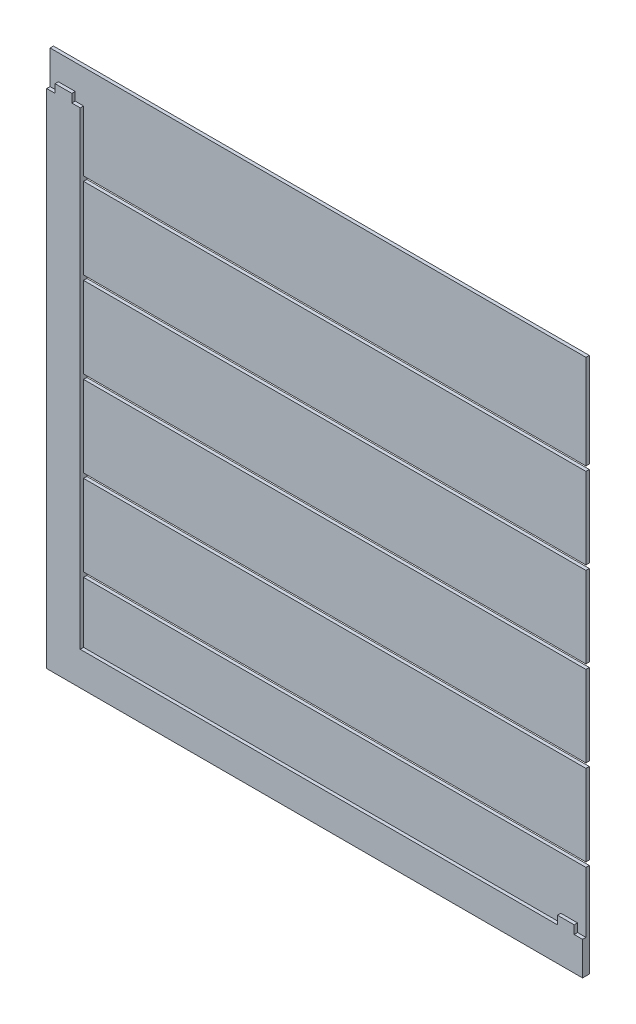
SolidWorks part; units mm, degrees
ref_plane "前视基准面" through (0, 0, 0) normal (0, 0, 1) x (1, 0, 0)
ref_plane "上视基准面" through (0, 0, 0) normal (0, 1, 0) x (1, 0, 0)
ref_plane "右视基准面" through (0, 0, 0) normal (1, 0, 0) x (0, 0, -1)
sketch "草图1" plane through (0, 0, 0) normal (0, 0, 1) x (1, 0, 0)
  line L0 (-75, 51.8686) -> (75, 51.8686)
  line L5 (75, 79.9686) -> (75, 51.8686)
  line L6 (75, 50.4686) -> (75, 26.2686)
  line L7 (-75, 50.4686) -> (75, 50.4686)
  line L8 (75, 24.8686) -> (75, 0.6686)
  line L9 (-75, 50.4686) -> (-75, 51.8686)
  line L10 (-75, 51.8686) -> (-75, 51.1686) construction
  line L11 (-75, 51.1686) -> (75, 51.1686) construction
  line L12 (-75, 51.8686) -> (75, 51.8686)
  line L13 (-75, 24.8686) -> (-75, 26.2686)
  line L14 (75, -0.7314) -> (75, -24.9314)
  line L15 (75, -26.3314) -> (75, -50.5314)
  line L16 (-65, 51.8686) -> (75, 51.8686)
  line L17 (-65, 50.4686) -> (75, 50.4686)
  line L18 (75, -51.9314) -> (75, -80.0314)
  line L19 (-65, 51.8686) -> (75, 51.8686)
  line L20 (-75, -0.7314) -> (-75, 0.6686)
  line L21 (-65, 51.1686) -> (75, 51.1686) construction
  line L22 (75, 79.9686) -> (-85, 79.9686)
  line L23 (-85, 79.9686) -> (-85, -80.0314)
  line L24 (-65, 26.2686) -> (75, 26.2686)
  line L25 (-65, 24.8686) -> (75, 24.8686)
  line L27 (-65, 26.2686) -> (75, 26.2686)
  line L29 (-65, 25.5686) -> (75, 25.5686) construction
  line L30 (-85, -80.0314) -> (75, -80.0314)
  line L32 (-65, 0.6686) -> (75, 0.6686)
  line L33 (-65, -0.7314) -> (75, -0.7314)
  line L35 (-65, 0.6686) -> (75, 0.6686)
  line L37 (-65, -0.0314) -> (75, -0.0314) construction
  line L45 (-65, -25.6314) -> (75, -25.6314) construction
  line L47 (-75, -26.3314) -> (-75, -24.9314)
  line L50 (-75, -0.0314) -> (-85, -0.0314) construction
  line L54 (-75, -51.9314) -> (-75, -50.5314)
  line L56 (-75, 26.2686) -> (75, 26.2686)
  line L57 (-75, 24.8686) -> (75, 24.8686)
  line L59 (-75, 26.2686) -> (75, 26.2686)
  line L61 (-75, 25.5686) -> (75, 25.5686) construction
  line L64 (-75, 0.6686) -> (75, 0.6686)
  line L65 (-75, -0.7314) -> (75, -0.7314)
  line L67 (-75, 0.6686) -> (75, 0.6686)
  line L69 (-75, -0.0314) -> (75, -0.0314) construction
  line L72 (-75, -24.9314) -> (75, -24.9314)
  line L73 (-75, -26.3314) -> (75, -26.3314)
  line L75 (-75, -24.9314) -> (75, -24.9314)
  line L77 (-75, -25.6314) -> (75, -25.6314) construction
  line L80 (-75, -50.5314) -> (75, -50.5314)
  line L81 (-75, -51.9314) -> (75, -51.9314)
  line L83 (-75, -50.5314) -> (75, -50.5314)
  line L85 (-75, -51.2314) -> (75, -51.2314) construction
  line L101 (-65, -26.3314) -> (75, -26.3314) [skipped]
  line L102 (-65, -24.9314) -> (75, -24.9314) [skipped]
  line L103 (-65, -24.9314) -> (75, -24.9314) [skipped]
  line L105 (-65, -50.5314) -> (75, -50.5314) [skipped]
  line L106 (-65, -50.5314) -> (75, -50.5314) [skipped]
  line L107 (-65, -51.9314) -> (75, -51.9314) [skipped]
  line L108 (-65, -51.2314) -> (75, -51.2314) construction
  point P0 (0, 0)
  point P3 (-85, -0.0314)
  dimension "D1" = 160
  dimension "D2" = 160
  dimension "D3" = 1.4
  dimension "D5" = 2
  dimension "D7" = 25.6
  dimension "D6" = 5
extrude "凸台-拉伸1" add sketch "草图1" along normal blind 1
sketch "草图2" plane through (0, 0, 1) normal (0, 0, 1) x (1, 0, 0)
  line L0 (-85, -80.0314) -> (-85, -70.0314)
  line L1 (-85, 79.9686) -> (-85, -80.0314) construction
  line L2 (-75, -70.0314) -> (67.5, -70.0314)
  line L3 (75, -80.0314) -> (75, -51.9314) construction
  line L4 (75, -70.0314) -> (75, -80.0314)
  line L5 (75, -80.0314) -> (-85, -80.0314)
  line L6 (-75, -70.0314) -> (-75, 69.9686)
  line L7 (-80, 72.4686) -> (-80, 75.0021) construction
  line L9 (-85, 69.9686) -> (-85, -70.0314)
  line L10 (-85, 69.9686) -> (-82.5, 69.9686)
  line L11 (-82.5, 69.9686) -> (-82.5, 72.4686)
  line L12 (-82.5, 72.4686) -> (-77.5, 72.4686)
  line L13 (-77.5, 69.9686) -> (-75, 69.9686)
  line L14 (75, 79.9686) -> (-85, 79.9686) construction
  line L15 (-77.5, 69.9686) -> (-77.5, 72.4686)
  line L16 (72.5, -70.0314) -> (72.5, -67.5314)
  line L17 (72.5, -67.5314) -> (67.5, -67.5314)
  line L18 (67.5, -67.5314) -> (67.5, -70.0314)
  line L19 (75, -51.9314) -> (75, -80.0314) construction
  line L20 (72.5, -70.0314) -> (75, -70.0314)
  dimension "D1" = 10
  dimension "D2" = 10
  dimension "D3" = 5
  dimension "D4" = 2.5
  dimension "D5" = 10
  dimension "D6" = 2.5
  dimension "D7" = 2.5
extrude "凸台-拉伸2" add sketch "草图2" along normal blind 1
